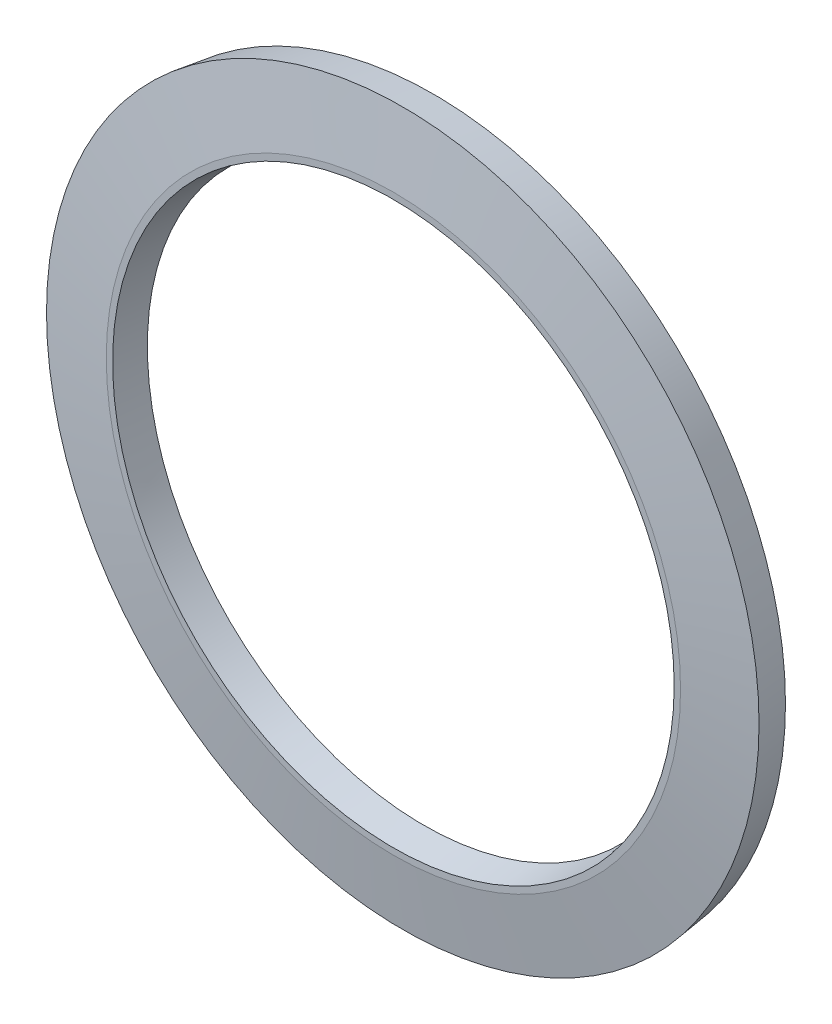
SolidWorks part; units mm, degrees
material "SPRING STEEL ASTM A 229"
ref_plane "Front Plane" through (0, 0, 0) normal (0, 0, 1) x (1, 0, 0)
ref_plane "Top Plane" through (0, 0, 0) normal (0, 1, 0) x (1, 0, 0)
ref_plane "Right Plane" through (0, 0, 0) normal (1, 0, 0) x (0, 0, -1)
sketch "Sketch1" plane through (0, 0, 0) normal (1, 0, 0) x (0, 0, -1)
  line L0 (0, 0) -> (94.7517, 0) construction
  line L1 (1.4787, 56.15) -> (6.3, 55.4957)
  line L2 (6.3, 52.2797) -> (6.3, 29.708) construction
  line L3 (6.3, 54.4957) -> (4.8213, 43.6)
  line L4 (1.4787, 56.15) -> (0, 45.2543)
  line L5 (0, 44.2543) -> (4.8213, 43.6)
  line L6 (0, 45.2543) -> (0, 44.2543)
  line L7 (6.3, 55.4957) -> (6.3, 54.4957)
  dimension "D1" = 112.3
  dimension "D2" = 5
  dimension "D3" = 87.2
  dimension "D4" = 1
  dimension "D5" = 1
  dimension "D6" = 6.3
revolve "Revolve1" add sketch "Sketch1" angle 360 about L0
